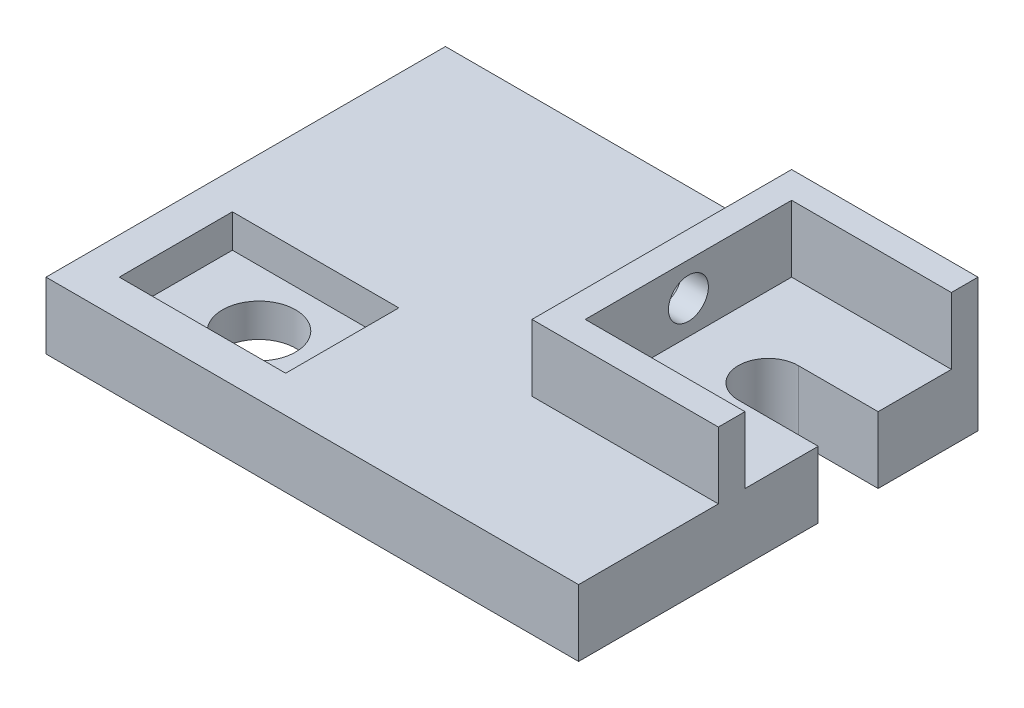
SolidWorks part; units mm, degrees
ref_plane "Спереди" through (0, 0, 0) normal (0, 0, 1) x (1, 0, 0)
ref_plane "Сверху" through (0, 0, 0) normal (0, 1, 0) x (1, 0, 0)
ref_plane "Справа" through (0, 0, 0) normal (1, 0, 0) x (0, 0, -1)
sketch "Эскиз1" plane through (0, 0, 0) normal (0, 1, 0) x (1, 0, 0)
  line L1 (-40, -30) -> (40, -30)
  line L2 (-40, -30) -> (-40, 30)
  line L3 (-40, 30) -> (40, 30)
  line L4 (40, -30) -> (40, 30)
  line L5 (-40, -30) -> (40, 30) construction
  line L6 (-40, 30) -> (40, -30) construction
  point P0 (0, 0)
  dimension "D1" = 80
  dimension "D2" = 60
extrude "Бобышка-Вытянуть1" add sketch "Эскиз1" along normal blind 10
sketch "Эскиз2" plane through (0, 10, 0) normal (0, 1, 0) x (1, 0, 0)
  line L0 (28, 6) -> (40, 6)
  line L1 (40, -30) -> (40, 30) construction
  line L2 (40, 6) -> (40, 15)
  line L3 (40, 15) -> (28, 15)
  line L4 (40, 30) -> (-40, 30) construction
  line L5 (-40, 30) -> (-40, -30) construction
  line L6 (-40, -30) -> (40, -30) construction
  circle A0 centre (28, 10.5) radius 4.5
  circle A1 centre (-22, -16) radius 5.5
  line M1 (40, -30) -> (40, 30)
  dimension "D1" = 9
  dimension "D4" = 11
  dimension "D2" = 12
  dimension "D3" = 15
  dimension "D5" = 18
  dimension "D6" = 14
extrude "Вырез-Вытянуть1" cut sketch "Эскиз2" against normal through all contours A1 | A0 | A0 L0 L3 M1
sketch "Эскиз4" plane through (0, 10, 0) normal (0, 1, 0) x (1, 0, 0)
  line L0 (40, -5) -> (16, -5)
  line L1 (40, 30) -> (12, 30)
  line L2 (40, 30) -> (40, -9)
  line L3 (40, -9) -> (12, -9)
  line L4 (12, 30) -> (12, -9)
  line L5 (16, 26) -> (16, -5)
  line L6 (40, 26) -> (16, 26)
  line L7 (16, 10.5) -> (40, 10.5) construction
  line L8 (23.5, 10.5) -> (40, 10.5) construction
  arc A0 (28, 15) -> (28, 6) centre (28, 10.5) ccw construction
  line M8 (40, 30) -> (-40, 30)
  line M11 (40, -30) -> (40, 6)
  dimension "D2" = 28
  dimension "D1" = 4
extrude "Бобышка-Вытянуть2" add sketch "Эскиз4" along normal blind 10 contours L6 L2 L4 L3 L0 L5 M8 M11
sketch "Эскиз5" plane through (16, 0, 0) normal (1, 0, 0) x (0, 0, -1)
  line L0 (10.5, 20) -> (10.5, 10) construction
  line L1 (26, 20) -> (-5, 20) construction
  line L2 (15, 10) -> (6, 10) construction
  circle A0 centre (10.5, 15) radius 3
  dimension "D1" = 6
extrude "Вырез-Вытянуть3" cut sketch "Эскиз5" against normal through all
sketch "Эскиз6" plane through (0, 10, 0) normal (0, 1, 0) x (1, 0, 0)
  line L0 (-22, -16) -> (-40, -16) construction
  line L1 (-40, 30) -> (-40, -30) construction
  line L3 (-9.5, -24.5) -> (-34.5, -24.5)
  line L4 (-9.5, -24.5) -> (-9.5, -7.5)
  line L5 (-9.5, -7.5) -> (-34.5, -7.5)
  line L6 (-34.5, -24.5) -> (-34.5, -7.5)
  line L7 (-9.5, -24.5) -> (-34.5, -7.5) construction
  line L8 (-9.5, -7.5) -> (-34.5, -24.5) construction
  point P5 (-22, -16)
  dimension "D1" = 17
  dimension "D3" = 25
extrude "Вырез-Вытянуть4" cut sketch "Эскиз6" against normal blind 5 contours L3 L6 L5 L4
